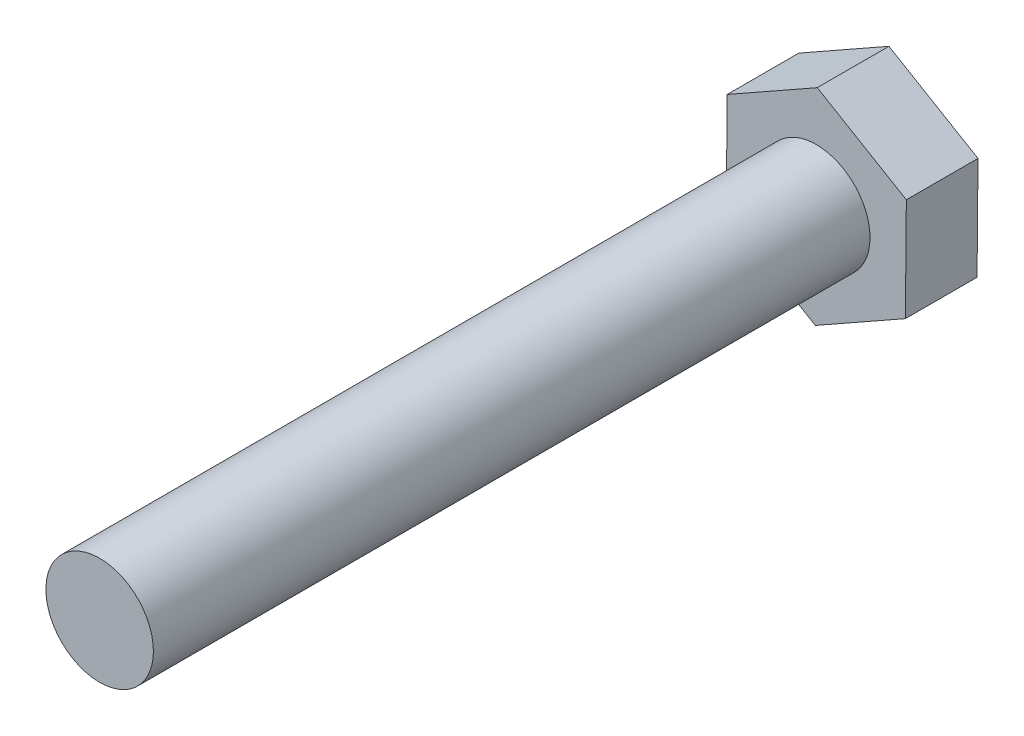
SolidWorks part; units mm, degrees
material "Нержавеющая сталь (ферритная)"
ref_plane "Front" through (0, 0, 0) normal (0, 0, 1) x (1, 0, 0)
ref_plane "Top" through (0, 0, 0) normal (0, 1, 0) x (1, 0, 0)
ref_plane "Right" through (0, 0, 0) normal (1, 0, 0) x (0, 0, -1)
sketch "Эскиз1" plane through (0, 0, 0) normal (0, 0, 1) x (1, 0, 0)
  line L1 (4.9735, -2.9321) -> (5.0261, 2.8411)
  line L2 (5.0261, 2.8411) -> (0.0526, 5.7733)
  line L3 (0.0526, 5.7733) -> (-4.9735, 2.9321)
  line L4 (-4.9735, 2.9321) -> (-5.0261, -2.8411)
  line L5 (-5.0261, -2.8411) -> (-0.0526, -5.7733)
  line L6 (-0.0526, -5.7733) -> (4.9735, -2.9321)
  circle A0 centre (0, 0) radius 5 construction
  dimension "D1" = 10
extrude "Бобышка-Вытянуть1" add sketch "Эскиз1" along normal blind 4
sketch "Эскиз2" plane through (0, 0, 4) normal (0, 0, 1) x (1, 0, 0)
  circle A0 centre (0, 0) radius 3
extrude "Бобышка-Вытянуть2" add sketch "Эскиз2" along normal blind 40
